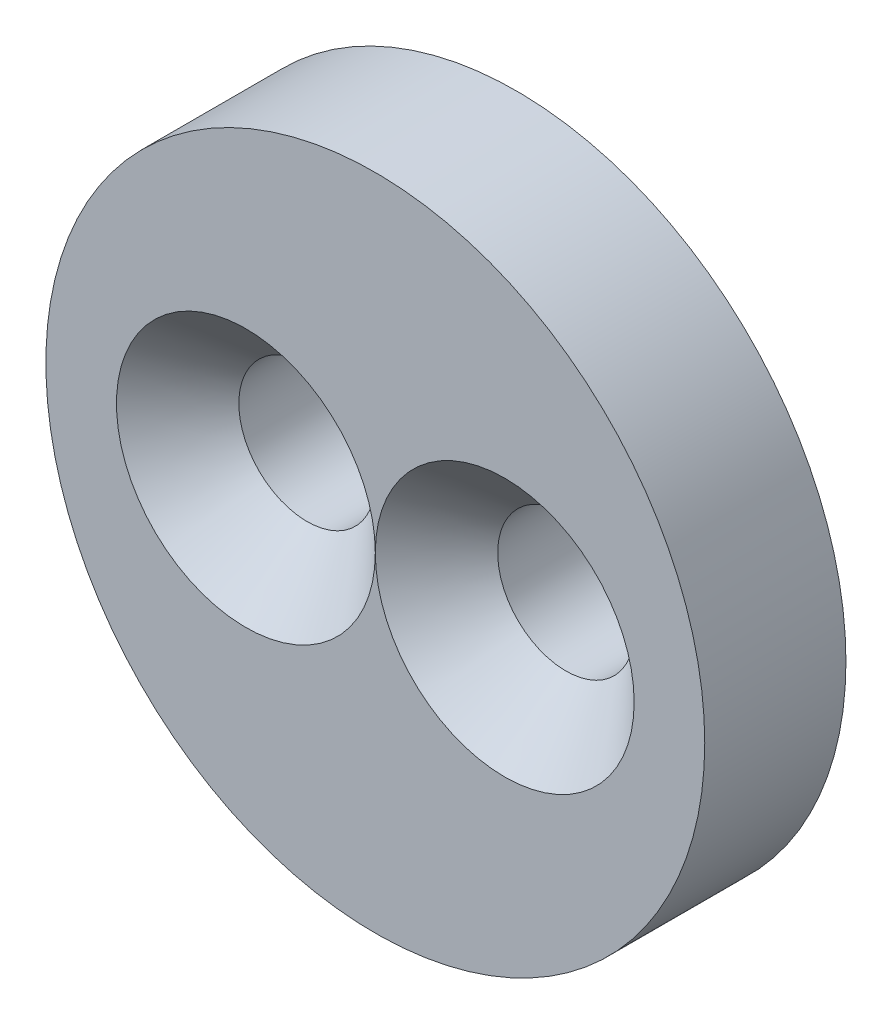
SolidWorks part; units mm, degrees
material "eSUN Tough Resin"
ref_plane "Front Plane" through (0, 0, 0) normal (0, 0, 1) x (1, 0, 0)
ref_plane "Top Plane" through (0, 0, 0) normal (0, 1, 0) x (1, 0, 0)
ref_plane "Right Plane" through (0, 0, 0) normal (1, 0, 0) x (0, 0, -1)
sketch "Sketch1" plane through (0, 0, 26.85) normal (0, 0, 1) x (1, 0, 0)
  circle A0 centre (0, 0) radius 7
  circle A1 centre (0, 0) radius 7.4923 construction
  dimension "D1" = 14
extrude "Boss-Extrude1" add sketch "Sketch1" along normal blind 3
hole_wizard "CSK for M2.5 Countersunk Flat Head Screw1" positions "Sketch2" profile "Sketch4" countersink size "M2.5" standard "ISO" end condition through all
sketch "Sketch2" plane through (0, 0, 29.85) normal (0, 0, 1) x (1, 0, 0)
  point P0 (-2.75, 0)
  point P3 (2.75, 0)
sketch "Sketch4" plane through (-2.75, 0, 29.85) normal (1, 0, 0) x (0, -1, 0)
  line L0 (0, 0) -> (0, 3)
  line L1 (0, 3) -> (1.45, 3)
  line L2 (1.45, 3) -> (1.45, 1.3)
  line L3 (1.45, 1.3) -> (2.75, 0)
  line L5 (2.75, 0) -> (0, 0)
  line L6 (-1.45, 1.3) -> (-2.75, 0) construction
  line L11 (0, -6.35) -> (0, 107.95) construction
  dimension "Thru Hole Dia." = 2.9
  dimension "Thru Hole Depth" = 3
  dimension "Near C'Sink Dia." = 5.5
  dimension "Near C'Sink Angle" = 90
